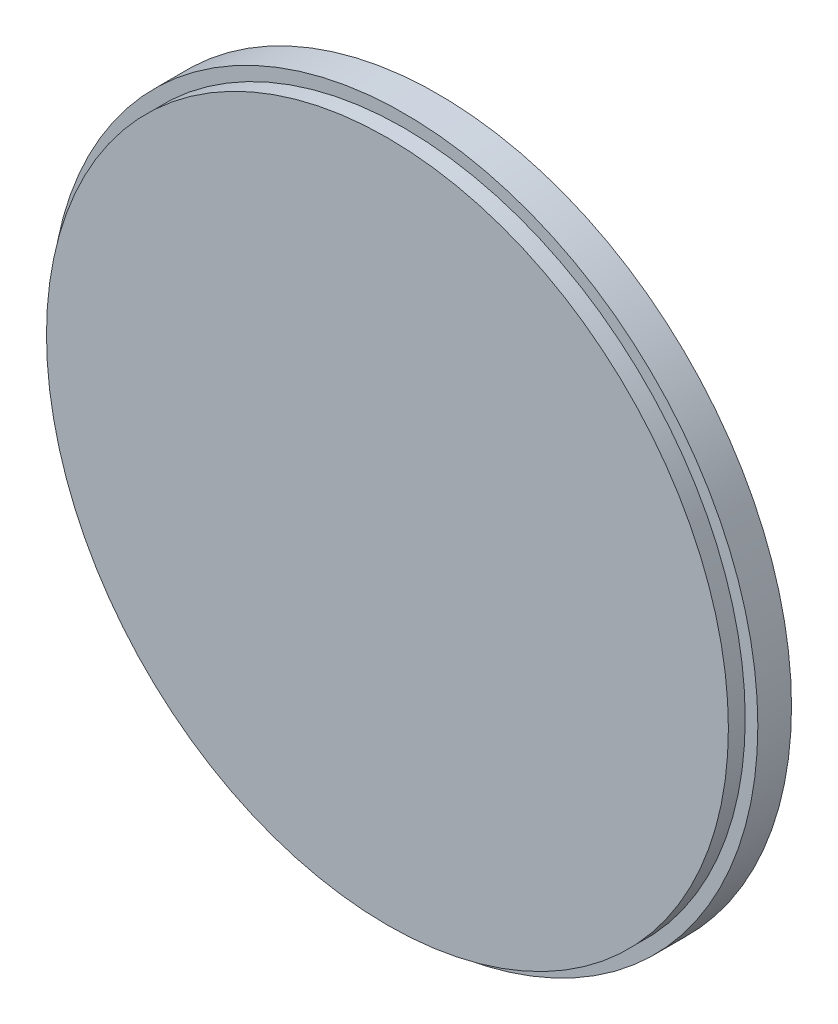
SolidWorks part; units mm, degrees
ref_plane "Front Plane" through (0, 0, 0) normal (0, 0, 1) x (1, 0, 0)
ref_plane "Top Plane" through (0, 0, 0) normal (0, 1, 0) x (1, 0, 0)
ref_plane "Right Plane" through (0, 0, 0) normal (1, 0, 0) x (0, 0, -1)
sketch "Sketch1" plane through (0, 0, 0) normal (0, 0, 1) x (1, 0, 0)
  circle A0 centre (0, 0) radius 21
  dimension "D1" = 42
extrude "Boss-Extrude1" add sketch "Sketch1" along normal blind 2
sketch "Sketch2" plane through (0, 0, 2) normal (0, 0, 1) x (1, 0, 0)
  circle A0 centre (0, 0) radius 20.25
  dimension "D1" = 40.5
extrude "Boss-Extrude2" add sketch "Sketch2" along normal blind 1
